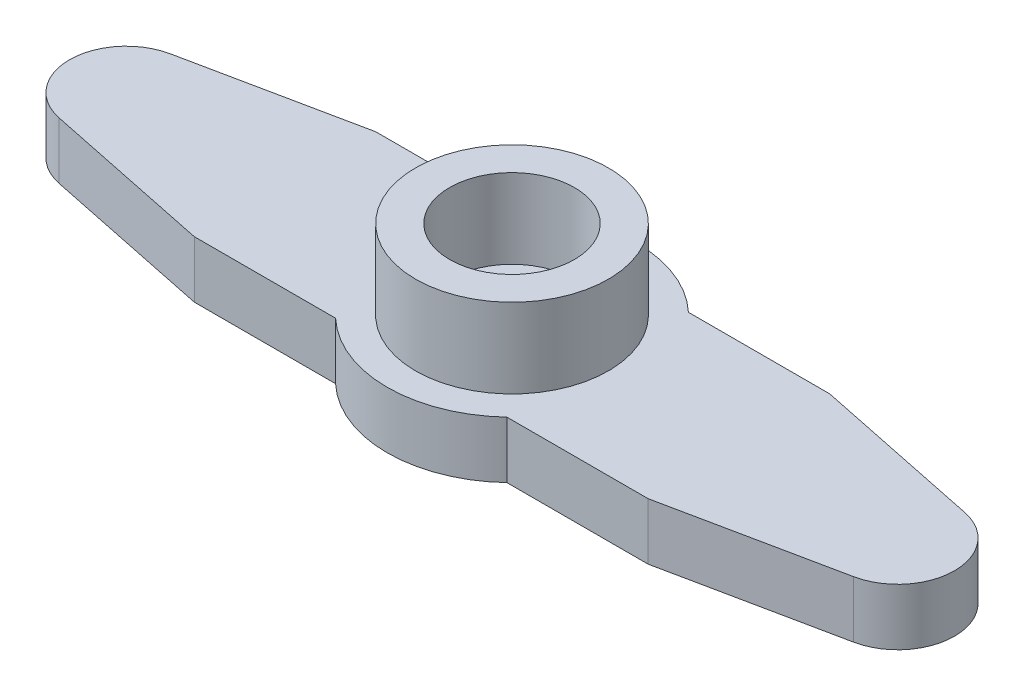
SolidWorks part; units mm, degrees
ref_plane "Front Plane" through (0, 0, 0) normal (0, 0, 1) x (1, 0, 0)
ref_plane "Top Plane" through (0, 0, 0) normal (0, 1, 0) x (1, 0, 0)
ref_plane "Right Plane" through (0, 0, 0) normal (1, 0, 0) x (0, 0, -1)
sketch "Sketch1" plane through (0, 0, 0) normal (0, 1, 0) x (1, 0, 0)
  line L0 (0, 0) -> (19.5, 0) construction
  line L1 (0, 0) -> (-19.5, 0) construction
  line L2 (0, 4) -> (19.5, 4)
  line L3 (0, 4) -> (-19.5, 4)
  line L4 (0, -4) -> (19.5, -4)
  line L5 (0, -4) -> (-19.5, -4)
  line L6 (-19.5, 0) -> (-14.5, 0)
  line L7 (0, 0) -> (0, 2.9358)
  line L8 (0, 4) -> (-10, 4)
  line L9 (-17.5061, 2.4482) -> (-10, 4)
  line L10 (-17.5061, -2.4482) -> (-10, -4)
  line L11 (17.5061, -2.4482) -> (10, -4)
  line L12 (17.5061, 2.4482) -> (10, 4)
  circle A0 centre (0, 0) radius 5.5
  circle A1 centre (-17, 0) radius 2.5
  circle A2 centre (17, 0) radius 2.5
  dimension "D1" = 11
  dimension "D2" = 19.5
  dimension "D3" = 19.5
  dimension "D6" = 5
  dimension "D7" = 10
  dimension "D4" = 4
  dimension "D5" = 4
extrude "Boss-Extrude1" add sketch "Sketch1" along normal blind 2.5
sketch "Sketch2" plane through (0, 2.5, 0) normal (0, 1, 0) x (1, 0, 0)
  circle A0 centre (0, 0) radius 1.5
  dimension "D1" = 3
extrude "Cut-Extrude1" cut sketch "Sketch2" against normal blind 10
sketch "Sketch3" plane through (0, 2.5, 0) normal (0, 1, 0) x (1, 0, 0)
  circle A0 centre (0, 0) radius 4.25
  circle A1 centre (0, 0) radius 2.75
  dimension "D1" = 8.5
  dimension "D2" = 5.5
extrude "Boss-Extrude2" add sketch "Sketch3" along normal blind 3.5
sketch "Sketch4" plane through (0, 0, 0) normal (0, -1, 0) x (1, 0, 0)
  circle A0 centre (0, 0) radius 3.75
  circle A1 centre (0, 0) radius 3.25
  dimension "D1" = 7.5
  dimension "D2" = 6.5
extrude "Boss-Extrude3" add sketch "Sketch4" along normal blind 0.5
